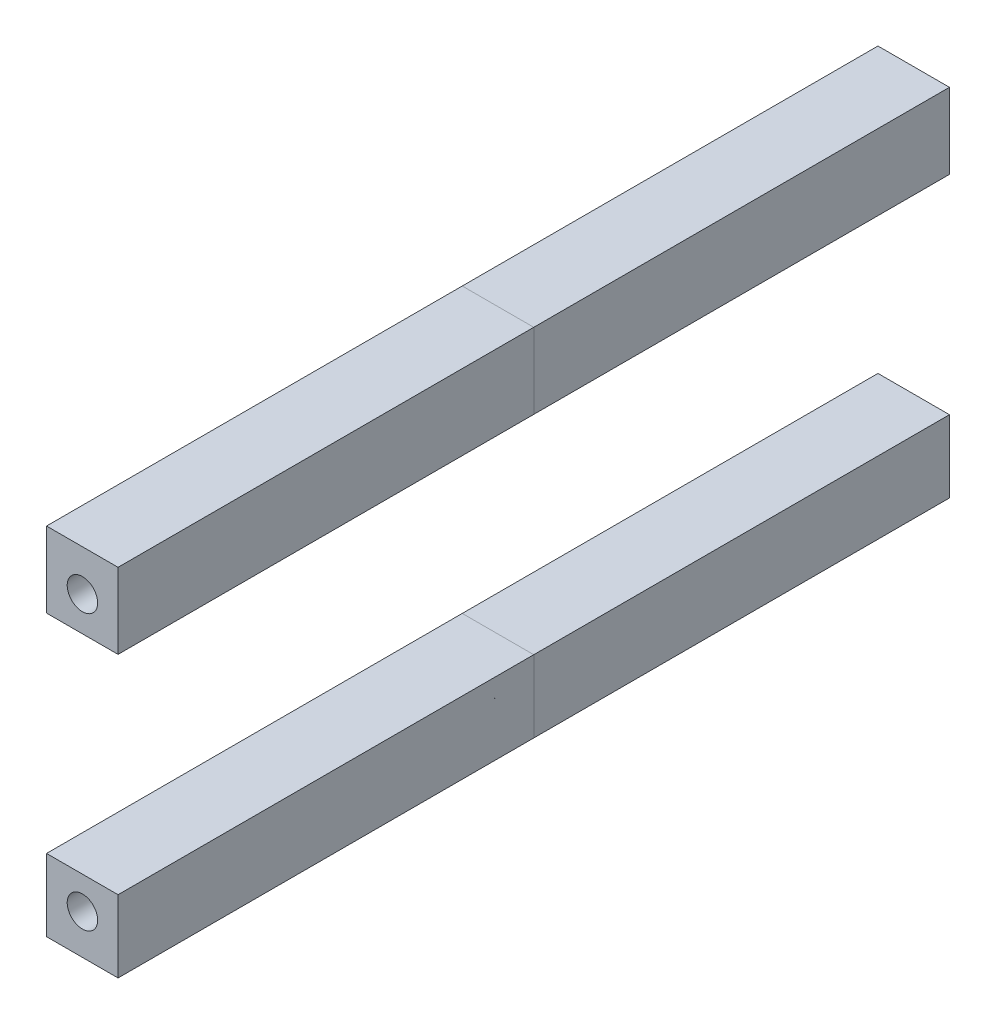
SolidWorks part; units mm, degrees
ref_plane "Front Plane" through (0, 0, 0) normal (0, 0, 1) x (1, 0, 0)
ref_plane "Top Plane" through (0, 0, 0) normal (0, 1, 0) x (1, 0, 0)
ref_plane "Right Plane" through (0, 0, 0) normal (1, 0, 0) x (0, 0, -1)
sketch "Sketch1" plane through (0, 0, 0) normal (0, 0, 1) x (1, 0, 0)
  line L1 (26.6683, -13.334) -> (42.6683, -13.334)
  line L2 (26.6683, -13.334) -> (26.6683, -70.666)
  line L3 (26.6683, -70.666) -> (42.6683, -70.666)
  line L4 (42.6683, -13.334) -> (42.6683, -70.666)
  circle A0 centre (34.6683, -19.4035) radius 2.25
  circle A1 centre (34.6683, -60.0435) radius 2.25
extrude "Boss-Extrude1" add sketch "Sketch1" against normal blind 12.7
sketch "Sketch4" plane through (0, 0, -12.7) normal (0, 0, -1) x (-1, 0, 0)
  line L0 (-42.6683, -13.334) -> (-26.6683, -13.334) construction
  line L1 (-39.9346, -13.334) -> (-29.3613, -13.334)
  line L2 (-39.9346, -13.334) -> (-39.9346, -24.4883)
  line L3 (-39.9346, -24.4883) -> (-29.3613, -24.4883)
  line L4 (-29.3613, -13.334) -> (-29.3613, -24.4883)
  line L5 (-42.6683, -70.666) -> (-42.6683, -13.334) construction
  line L6 (-42.6683, -42) -> (-26.6683, -42) construction
  line L7 (-26.6683, -13.334) -> (-26.6683, -70.666) construction
  line L8 (-39.9346, -55.2598) -> (-29.3613, -55.2598)
  line L9 (-29.3613, -65.9263) -> (-29.3613, -55.2598)
  line L10 (-39.9346, -65.9263) -> (-29.3613, -65.9263)
  line L11 (-39.9346, -65.9263) -> (-39.9346, -55.2598)
  circle A0 centre (-34.6683, -19.4035) radius 2.25
  circle A1 centre (-34.6683, -60.0435) radius 2.25
ref_plane "Plane2" through (0, -42, 0) normal (0, 1, 0) x (1, 0, 0)
extrude "Boss-Extrude3" add sketch "Sketch4" along normal blind 48.768 and the other way blind 12.7
sketch "Sketch5" plane through (0, 0, -12.7) normal (0, 0, -1) x (-1, 0, 0)
  line L0 (-39.9346, -13.334) -> (-42.6683, -13.334)
  line L1 (-42.6683, -13.334) -> (-42.6683, -70.666)
  line L2 (-42.6683, -70.666) -> (-26.6683, -70.666)
  line L3 (-26.6683, -70.666) -> (-26.6683, -13.334)
  line L4 (-26.6683, -13.334) -> (-29.3613, -13.334)
  line L5 (-29.3613, -13.334) -> (-29.3613, -24.4883)
  line L6 (-29.3613, -24.4883) -> (-39.9346, -24.4883)
  line L7 (-39.9346, -24.4883) -> (-39.9346, -13.334)
  line L8 (-39.9346, -55.2598) -> (-39.9346, -65.9263)
  line L9 (-39.9346, -65.9263) -> (-29.3613, -65.9263)
  line L10 (-29.3613, -65.9263) -> (-29.3613, -55.2598)
  line L11 (-29.3613, -55.2598) -> (-39.9346, -55.2598)
extrude "Cut-Extrude1" cut sketch "Sketch5" against normal blind 47.752
mirror "Mirror3" about plane through (0, 0, -61.468) normal (0, 0, -1) of bodies 107 106
